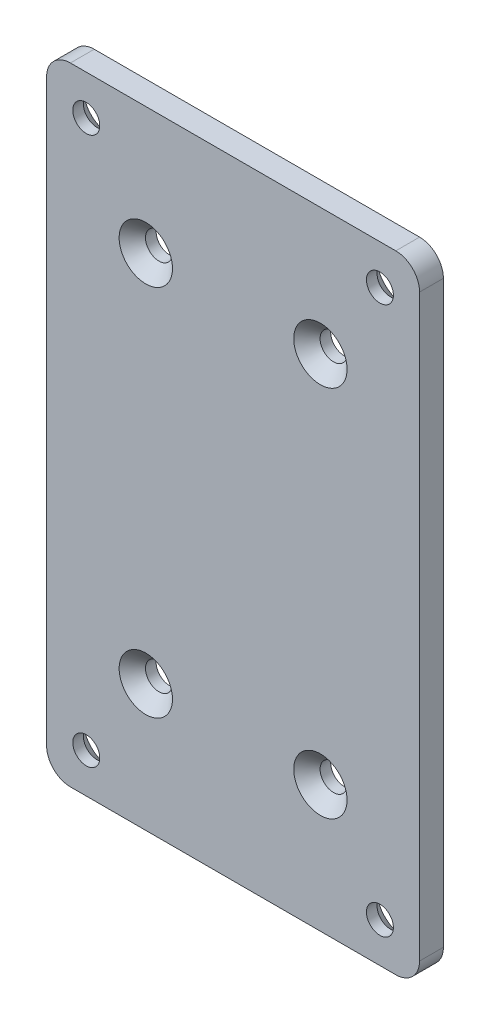
SolidWorks part; units mm, degrees
ref_plane "Спереди" through (0, 0, 0) normal (0, 0, 1) x (1, 0, 0)
ref_plane "Сверху" through (0, 0, 0) normal (0, 1, 0) x (1, 0, 0)
ref_plane "Справа" through (0, 0, 0) normal (1, 0, 0) x (0, 0, -1)
sketch "Эскиз1" plane through (0, 0, 0) normal (0, 0, 1) x (1, 0, 0)
  line L1 (-23.5, 39.5) -> (23.5, 39.5)
  line L2 (-23.5, 39.5) -> (-23.5, -39.5)
  line L3 (-23.5, -39.5) -> (23.5, -39.5)
  line L4 (23.5, 39.5) -> (23.5, -39.5)
  line L5 (-23.5, 39.5) -> (23.5, -39.5) construction
  line L6 (-23.5, -39.5) -> (23.5, 39.5) construction
  point P0 (0, 0)
  dimension "D1" = 47
  dimension "D2" = 79
extrude "Бобышка-Вытянуть1" add sketch "Эскиз1" along normal blind 3
sketch "Эскиз2" plane through (0, 0, 3) normal (0, 0, 1) x (1, 0, 0)
  line L1 (-11, 23.5) -> (11, 23.5) construction
  line L2 (-11, 23.5) -> (-11, -23.5) construction
  line L3 (-11, -23.5) -> (11, -23.5) construction
  line L4 (11, 23.5) -> (11, -23.5) construction
  line L5 (-11, 23.5) -> (11, -23.5) construction
  line L6 (-11, -23.5) -> (11, 23.5) construction
  point P0 (0, 0)
  dimension "D1" = 22
  dimension "D2" = 47
hole_wizard "Зенковка для  винта с потайной головкой с внутренним шестигранником M31" positions "Эскиз4" profile "Эскиз3" countersink size "M3" standard "Ansi Metric" end condition through all
sketch "Эскиз4" plane through (0, 0, 3) normal (0, 0, 1) x (1, 0, 0)
  point P0 (-11, 23.5)
  point P3 (11, 23.5)
  point P6 (-11, -23.5)
  point P9 (11, -23.5)
sketch "Эскиз3" plane through (-11, 23.5, 3) normal (1, 0, 0) x (0, -1, 0)
  line L0 (0, 0) -> (0, 3)
  line L1 (0, 3) -> (1.7, 3)
  line L2 (1.7, 3) -> (1.7, 1.66)
  line L3 (1.7, 1.66) -> (3.36, 0)
  line L5 (3.36, 0) -> (0, 0)
  line L6 (-1.7, 1.66) -> (-3.36, 0) construction
  line L11 (0, -6.35) -> (0, 107.95) construction
  dimension "Диаметр сквозного отверстия" = 3.4
  dimension "Глубина сквозного отверстия" = 3
  dimension "Диаметр передней зенковки" = 6.72
  dimension "Угол передней зенковки" = 90
sketch "Эскиз5" plane through (0, 0, 0) normal (0, 0, -1) x (-1, 0, 0)
  line L0 (-23.5, -39.5) -> (-23.5, 39.5) construction
  line L1 (-18.5, 34.5) -> (18.5, 34.5) construction
  line L2 (-18.5, 34.5) -> (-18.5, -34.5) construction
  line L3 (-18.5, -34.5) -> (18.5, -34.5) construction
  line L4 (18.5, 34.5) -> (18.5, -34.5) construction
  line L5 (-18.5, 34.5) -> (18.5, -34.5) construction
  line L6 (-18.5, -34.5) -> (18.5, 34.5) construction
  line L7 (-23.5, 39.5) -> (23.5, 39.5) construction
  point P0 (0, 0)
  dimension "D1" = 5
  dimension "D2" = 5
hole_wizard "Зенковка для  винта с потайной головкой с внутренним шестигранником M32" positions "Эскиз7" profile "Эскиз6" countersink size "M3" standard "Ansi Metric" end condition through all
sketch "Эскиз7" plane through (0, 0, 0) normal (0, 0, -1) x (-1, 0, 0)
  point P0 (-18.5, 34.5)
  point P3 (18.5, 34.5)
  point P6 (-18.5, -34.5)
  point P9 (18.5, -34.5)
sketch "Эскиз6" plane through (18.5, 34.5, 0) normal (1, 0, 0) x (0, 1, 0)
  line L0 (0, 0) -> (0, 3)
  line L1 (0, 3) -> (1.7, 3)
  line L2 (1.7, 3) -> (1.7, 1.66)
  line L3 (1.7, 1.66) -> (3.36, 0)
  line L5 (3.36, 0) -> (0, 0)
  line L6 (-1.7, 1.66) -> (-3.36, 0) construction
  line L11 (0, -6.35) -> (0, 107.95) construction
  dimension "Диаметр сквозного отверстия" = 3.4
  dimension "Глубина сквозного отверстия" = 3
  dimension "Диаметр передней зенковки" = 6.72
  dimension "Угол передней зенковки" = 90
fillet "Скругление1" radius 3 4 edges at (-23.5, 39.5, 1.5) (-23.5, -39.5, 1.5) (23.5, -39.5, 1.5) (23.5, 39.5, 1.5)
